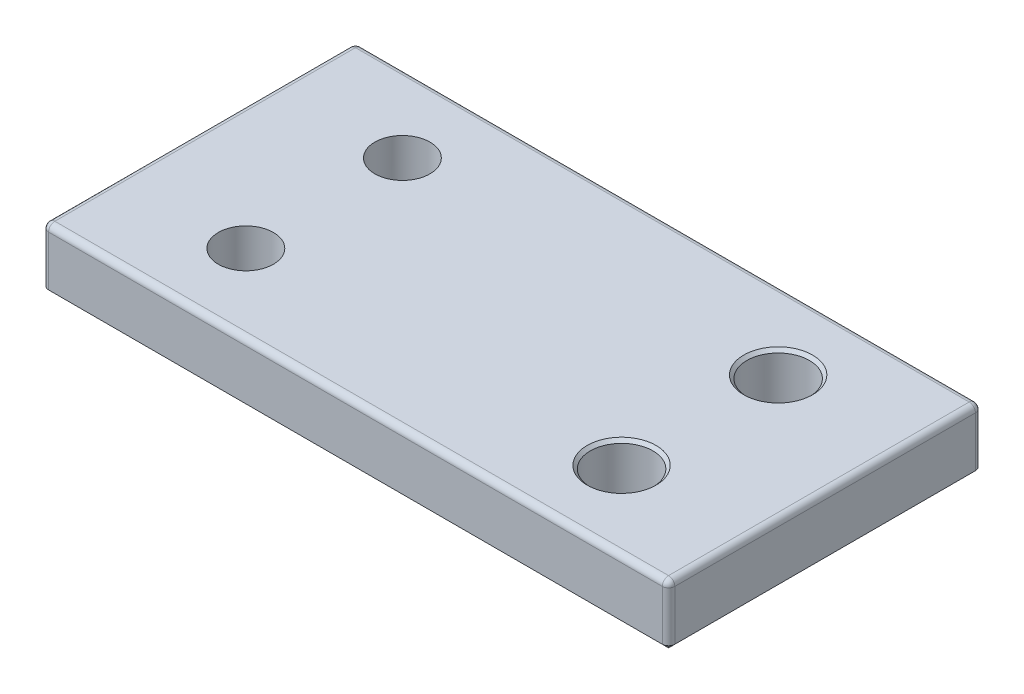
SolidWorks part; units mm, degrees
ref_plane "前基準面" through (0, 0, 0) normal (0, 0, 1) x (1, 0, 0)
ref_plane "上基準面" through (0, 0, 0) normal (0, 1, 0) x (1, 0, 0)
ref_plane "右基準面" through (0, 0, 0) normal (1, 0, 0) x (0, 0, -1)
sketch "草圖1" plane through (0, 0, 0) normal (0, 1, 0) x (1, 0, 0)
  line L1 (0, 0) -> (100, 0)
  line L2 (0, 0) -> (0, 50)
  line L3 (0, 50) -> (100, 50)
  line L4 (100, 0) -> (100, 50)
  dimension "D1" = 100
  dimension "D2" = 50
extrude "填料-伸長1" add sketch "草圖1" along normal blind 10
sketch "草圖2" plane through (0, 10, 0) normal (0, 1, 0) x (1, 0, 0)
  line L0 (0, 0) -> (100, 0) construction
  line L1 (20, 37.5) -> (80, 37.5)
  line L2 (20, 37.5) -> (20, 12.5)
  line L3 (20, 12.5) -> (80, 12.5)
  line L4 (80, 37.5) -> (80, 12.5)
  line L5 (0, 50) -> (0, 0) construction
  dimension "D1" = 25
  dimension "D2" = 12.5
  dimension "D3" = 20
  dimension "D4" = 60
hole_wizard "Ø10.0mm 定位孔1" positions "3D草圖2" profile "草圖4" hole size "Ø10.0" standard "ISO"
sketch3d "3D草圖2"
  point P0 (80, 10, -37.5)
  point P3 (80, 10, -12.5)
sketch "草圖4" plane through (80, 10, -37.5) normal (1, 0, 0) x (0, 0, 1)
  line L0 (0, 0) -> (0, 26.7543)
  line L1 (0, 26.7543) -> (5, 23.75)
  line L2 (5, 23.75) -> (5, 0)
  line L5 (5, 0) -> (0, 0)
  line L10 (0, 26.7543) -> (-5, 23.75) construction
  line L11 (0, -6.35) -> (0, 107.95) construction
  dimension "鑽孔直徑" = 10
  dimension "鑽孔深度" = 23.75
  dimension "導頭角度" = 118
hole_wizard "M10x1.25 螺紋孔1" positions "3D草圖1" profile "草圖3" tap size "M10x1.25" standard "ISO"
sketch3d "3D草圖1"
  point P0 (20, 10, -37.5)
  point P3 (20, 10, -12.5)
sketch "草圖3" plane through (20, 10, -37.5) normal (1, 0, 0) x (0, 0, 1)
  line L0 (0, 0) -> (0, 26.3938)
  line L1 (0, 26.3938) -> (4.4, 23.75)
  line L2 (4.4, 23.75) -> (4.4, 0)
  line L5 (4.4, 0) -> (0, 0)
  line L10 (0, 26.3938) -> (-4.4, 23.75) construction
  line L11 (0, -6.35) -> (0, 107.95) construction
  dimension "螺孔鑽直徑" = 8.8
  dimension "螺孔鑽深度" = 23.75
  dimension "導頭角度" = 118
cosmetic thread "鑽孔螺紋1" parameters "D1"=10, "D2"=10
cosmetic thread "鑽孔螺紋2" parameters "D1"=10, "D2"=10
fillet "圓角1" radius 1 4 edges at (100, 5, -50) (0, 5, -50) (0, 5, 0) (100, 5, 0)
chamfer "導角1" distance 1 angle 45 8 edges at (50, 0, -50) (0.2929, 0, -49.7071) (99.7071, 0, -49.7071) (0, 0, -25) (100, 0, -25) (0.2929, 0, -0.2929) (99.7071, 0, -0.2929) (50, 0, 0)
chamfer "導角2" distance 0.5 angle 45 2 edges at (80, 10, -32.5) (80, 10, -7.5)
fillet "圓角2" radius 1 8 edges at (0.2929, 10, -0.2929) (0, 10, -25) (0.2929, 10, -49.7071) (50, 10, -50) (99.7071, 10, -49.7071) (100, 10, -25) (99.7071, 10, -0.2929) (50, 10, 0)
